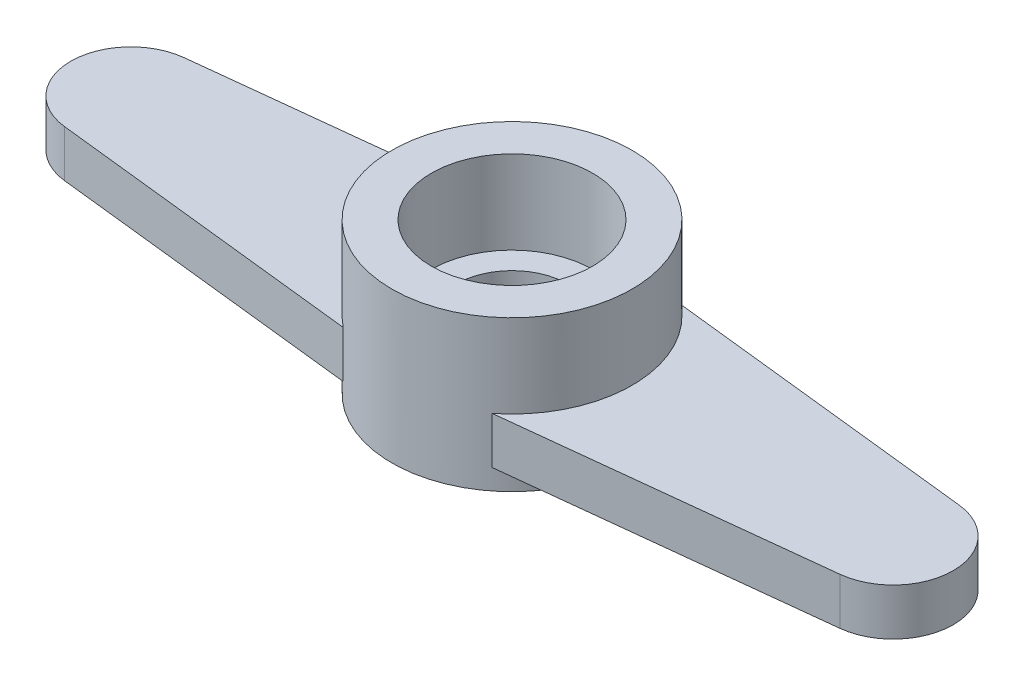
SolidWorks part; units mm, degrees
ref_plane "Front Plane" through (0, 0, 0) normal (0, 0, 1) x (1, 0, 0)
ref_plane "Top Plane" through (0, 0, 0) normal (0, 1, 0) x (1, 0, 0)
ref_plane "Right Plane" through (0, 0, 0) normal (1, 0, 0) x (0, 0, -1)
sketch "Sketch2" plane through (0, 0, 0) normal (0, 1, 0) x (1, 0, 0)
  line L0 (14.5, 0) -> (-14.5, 0) construction
  line L1 (0, 0) -> (0, 4.9815) construction
  line L2 (0, 0) -> (0, 3.1) construction
  line L3 (0, 3.1) -> (2.448, 3.1) construction
  line L4 (2.448, 3.1) -> (13.5476, 1.8741)
  line L5 (2.448, -3.1) -> (13.5476, -1.8741)
  line L6 (-2.448, -3.1) -> (-13.5476, -1.8741)
  line L7 (-2.448, 3.1) -> (-13.5476, 1.8741)
  circle A0 centre (12.525, 0) radius 1.975
  circle A1 centre (0, 0) radius 3.95
  circle A2 centre (-12.525, 0) radius 1.975
  point P4 (0, 0)
  dimension "D2" = 3.95
  dimension "D3" = 7.9
  dimension "D1" = 29
  dimension "D4" = 3.1
extrude "Boss-Extrude2" add sketch "Sketch2" along normal blind 1.54
sketch "Sketch3" plane through (0, 1.54, 0) normal (0, 1, 0) x (1, 0, 0)
  circle A0 centre (0, 0) radius 3.95
  arc A1 (2.448, 3.1) -> (-2.448, 3.1) centre (0, 0) ccw construction
extrude "Boss-Extrude3" add sketch "Sketch3" along normal blind 2.74
sketch "Sketch4" plane through (0, 0, 0) normal (0, -1, 0) x (-1, 0, 0)
  circle A0 centre (0, 0) radius 3.95
  arc A1 (-2.448, -3.1) -> (2.448, -3.1) centre (0, 0) ccw construction
extrude "Boss-Extrude4" add sketch "Sketch4" along normal blind 0.67
sketch "Sketch5" plane through (0, 4.28, 0) normal (0, 1, 0) x (1, 0, 0)
  circle A0 centre (0, 0) radius 2.65
  circle A1 centre (0, 0) radius 3.95 construction
  dimension "D1" = 1.3
extrude "Cut-Extrude1" cut sketch "Sketch5" against normal up to surface (2.74 mm away) up to face at (-5.461, 1.54, -0.775)
sketch "Sketch6" plane through (0, -0.67, 0) normal (0, -1, 0) x (-1, 0, 0)
  circle A0 centre (0, 0) radius 3.45
  circle A1 centre (0, 0) radius 3.95 construction
  dimension "D1" = 0.5
extrude "Cut-Extrude2" cut sketch "Sketch6" against normal up to surface (0.67 mm away) up to face at (-5.461, 0, 0.775)
sketch "Sketch7" plane through (0, 1.54, 0) normal (0, 1, 0) x (1, 0, 0)
  circle A0 centre (0, 0) radius 1.825
  dimension "D1" = 3.65
extrude "Cut-Extrude3" cut sketch "Sketch7" against normal through all
